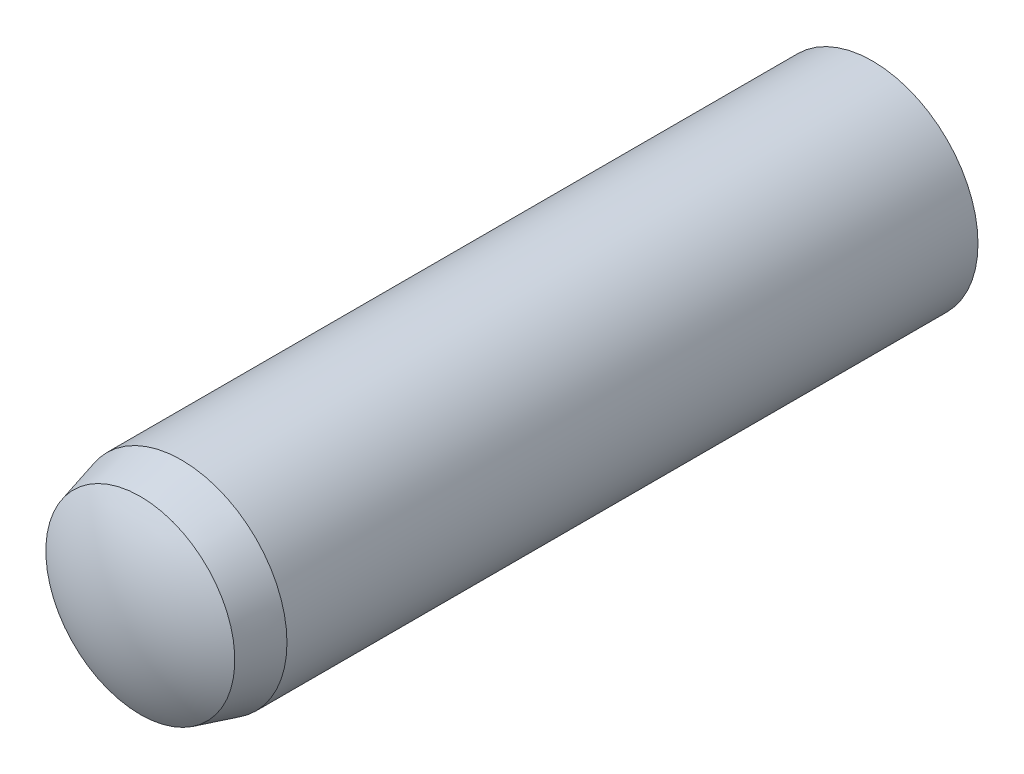
SolidWorks part; units mm, degrees
ref_plane "Front Plane" through (0, 0, 0) normal (0, 0, 1) x (1, 0, 0)
ref_plane "Top Plane" through (0, 0, 0) normal (0, 1, 0) x (1, 0, 0)
ref_plane "Right Plane" through (0, 0, 0) normal (1, 0, 0) x (0, 0, -1)
sketch "Sketch1" plane through (0, 0, 0) normal (0, 0, 1) x (1, 0, 0)
  circle A0 centre (0, 0) radius 4
  point P3 (0, 4)
  dimension "Diameter" = 8
sketch "Sketch2" plane through (0, 0, 0) normal (1, 0, 0) x (0, 0, -1)
  line L0 (-15, 0) -> (15, 0) construction
  line L1 (-15, 0) -> (-15, 4) construction
  line L2 (-15, 4) -> (15, 4)
  line L3 (15, 4) -> (15, 0) construction
  line L4 (-13.96, 3.582) -> (-12.4, 4)
  arc A0 (-15, 0) -> (-13.96, 3.582) centre (-8.3114, 0) cw
  arc A1 (15, 0) -> (13.8, 4) centre (7.7333, 0) ccw
  point P2 (0, 0)
  point P11 (-7, 0)
  point P13 (7, 0)
  dimension "Length" = 30
  dimension "D1" = 15
  dimension "D2" = 1.2
  dimension "D3" = 2.6
  dimension "D4" = 1.56
  dimension "D5" = 8
  dimension "D6" = 8
sketch "Sketch3" plane through (0, 0, 0) normal (1, 0, 0) x (0, 0, -1)
  line L0 (-15, 0) -> (15, 0) construction
  line L1 (-13.96, 3.582) -> (-12.4, 4) construction
  line L2 (-15, 0) -> (15, 0)
  line L3 (-13.96, 3.582) -> (-12.4, 4)
  line L4 (-12.4, 4) -> (13.8, 4)
  arc A0 (15, 0) -> (13.8, 4) centre (7.7333, 0) ccw construction
  arc A1 (-13.96, 3.582) -> (-15, 0) centre (-8.3114, 0) ccw construction
  arc A2 (15, 0) -> (13.8, 4) centre (7.7333, 0) ccw
  arc A3 (-13.96, 3.582) -> (-15, 0) centre (-8.3114, 0) ccw
revolve "Revolve1" add sketch "Sketch3" angle 360 about L2
equation "\"D2@Sketch2\" = \"Diameter@Sketch1\" * .15"
equation "\"D3@Sketch2\" = \"Diameter@Sketch1\" * .325"
equation "\"D4@Sketch2\" = \"D3@Sketch2\" * .6"
equation "\"D5@Sketch2\"=\"Diameter@Sketch1\""
equation "\"D6@Sketch2\"=\"D5@sketch2\""
